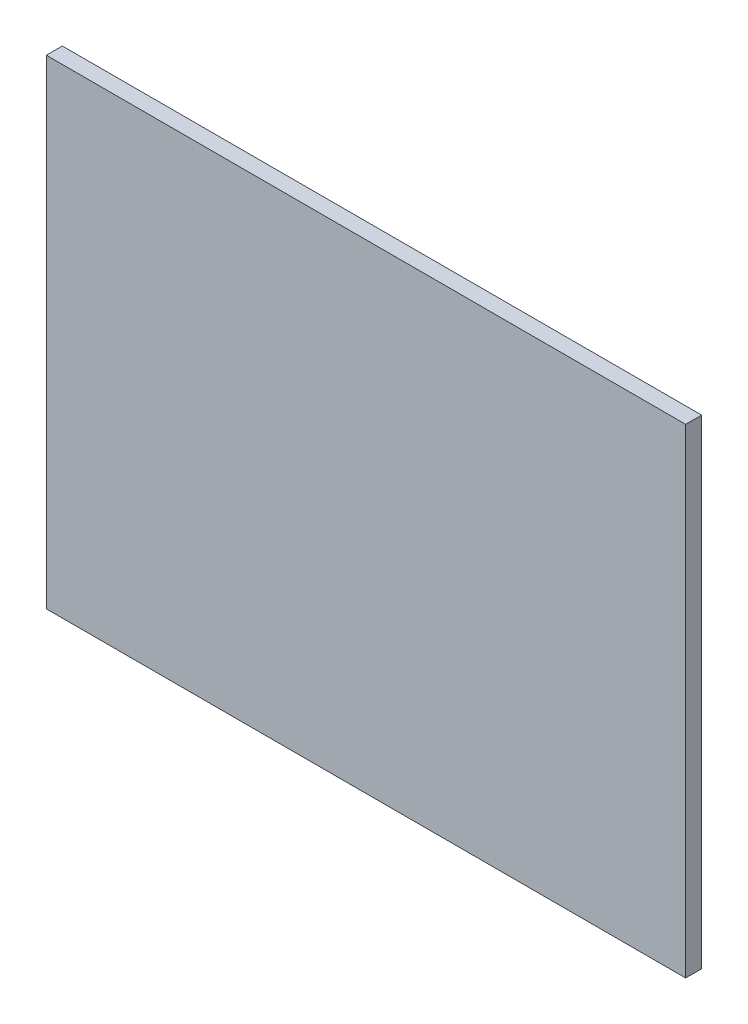
SolidWorks part; units mm, degrees
ref_plane "Front Plane" through (0, 0, 0) normal (1, 0, 0) x (0, 1, 0)
ref_plane "Top Plane" through (0, 0, 0) normal (0, 0, 1) x (0, 1, 0)
ref_plane "Right Plane" through (0, 0, 0) normal (0, 1, 0) x (-1, 0, 0)
sketch "Sketch1" plane through (0, 0, 0) normal (0, 0, 1) x (0, 1, 0)
  line L1 (-30, 40) -> (30, 40)
  line L2 (-30, 40) -> (-30, -40)
  line L3 (-30, -40) -> (30, -40)
  line L4 (30, 40) -> (30, -40)
  line L5 (-30, 40) -> (30, -40) construction
  line L6 (-30, -40) -> (30, 40) construction
  point P0 (0, 0)
  dimension "D1" = 80
  dimension "D2" = 60
extrude "Boss-Extrude1" add sketch "Sketch1" against normal blind 2 contours L1 L4 L3 L2
scale "Scale1" scale about centroid uniform scaling yes scale factor 0.7
